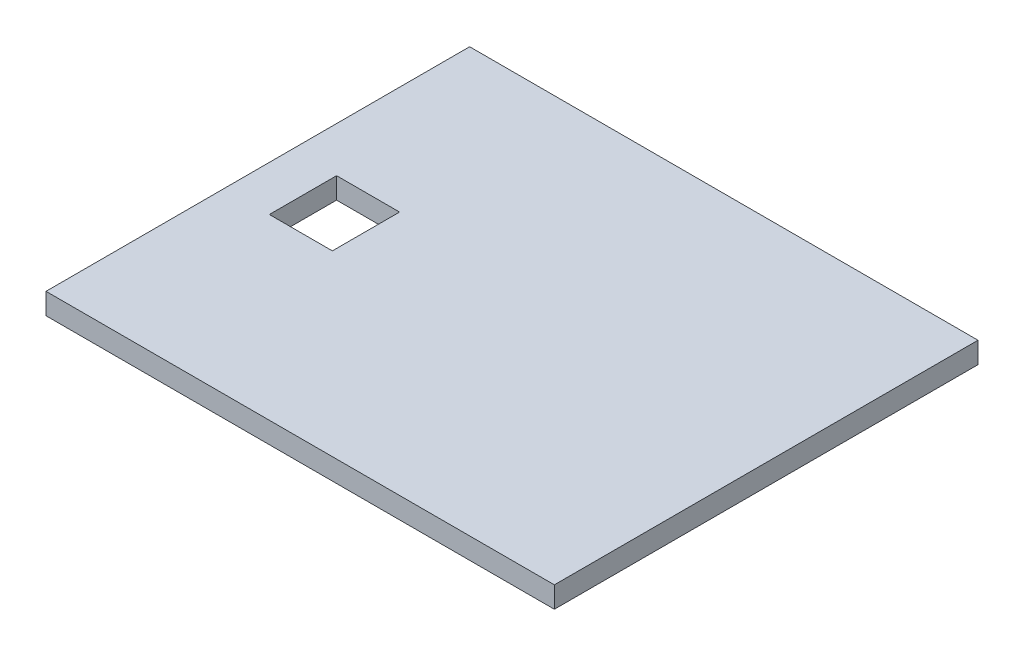
SolidWorks part; units mm, degrees
ref_plane "Front Plane" through (0, 0, 0) normal (0, 0, 1) x (1, 0, 0)
ref_plane "Top Plane" through (0, 0, 0) normal (0, 1, 0) x (1, 0, 0)
ref_plane "Right Plane" through (0, 0, 0) normal (1, 0, 0) x (0, 0, -1)
sketch "Sketch1" plane through (0, 0, 0) normal (0, 1, 0) x (1, 0, 0)
  line L0 (76.2, 0) -> (-76.2, 0) construction
  line L1 (76.2, -63.5) -> (-76.2, -63.5)
  line L2 (76.2, -63.5) -> (76.2, 63.5)
  line L3 (76.2, 63.5) -> (-76.2, 63.5)
  line L4 (-76.2, -63.5) -> (-76.2, 63.5)
  line L5 (76.2, -63.5) -> (-76.2, 63.5) construction
  line L6 (76.2, 63.5) -> (-76.2, -63.5) construction
  line L8 (-43.7782, -10.0762) -> (-62.6647, -10.0762)
  line L9 (-43.7782, -10.0762) -> (-43.7782, 10.0762)
  line L10 (-43.7782, 10.0762) -> (-62.6647, 10.0762)
  line L11 (-62.6647, -10.0762) -> (-62.6647, 10.0762)
  line L12 (-43.7782, -10.0762) -> (-62.6647, 10.0762) construction
  line L13 (-43.7782, 10.0762) -> (-62.6647, -10.0762) construction
  point P0 (0, 0)
  point P8 (-53.2215, 0)
  dimension "D1" = 127
  dimension "D2" = 152.4
extrude "Boss-Extrude1" add sketch "Sketch1" along normal blind 6.35
